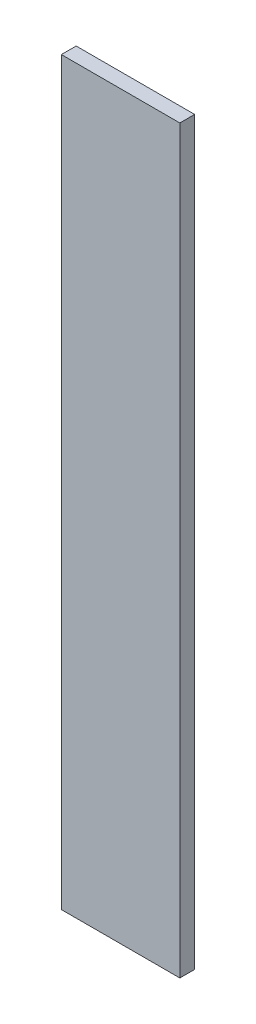
SolidWorks part; units mm, degrees
material "Plain Carbon Steel"
ref_plane "Front Plane" through (0, 0, 0) normal (0, 0, 1) x (1, 0, 0)
ref_plane "Top Plane" through (0, 0, 0) normal (0, 1, 0) x (1, 0, 0)
ref_plane "Right Plane" through (0, 0, 0) normal (1, 0, 0) x (0, 0, -1)
sketch "Sketch1" plane through (0, 0, 0) normal (0, 0, 1) x (1, 0, 0)
  line L1 (-270, -857.4627) -> (-30, -857.4627)
  line L2 (-270, -857.4627) -> (-270, 642.5373)
  line L3 (-270, 642.5373) -> (-30, 642.5373)
  line L4 (-30, -857.4627) -> (-30, 642.5373)
extrude "Boss-Extrude1" add sketch "Sketch1" against normal blind 30 contours L3 L4 L1 L2
ref_plane "Centre Plane" through (-150, 0, 0) normal (1, 0, 0) x (0, 0, -1)
